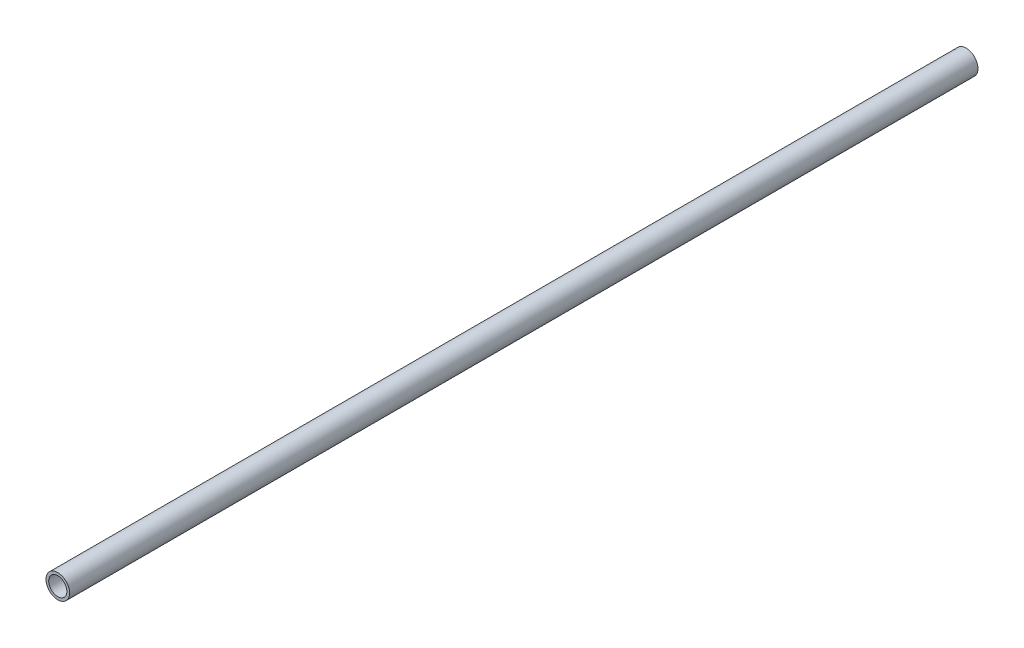
SolidWorks part; units mm, degrees
material "6061 Alloy"
ref_plane "Front Plane" through (0, 0, 0) normal (0, 0, 1) x (1, 0, 0)
ref_plane "Top Plane" through (0, 0, 0) normal (0, 1, 0) x (1, 0, 0)
ref_plane "Right Plane" through (0, 0, 0) normal (1, 0, 0) x (0, 0, -1)
sketch "Sketch1" plane through (0, 0, 0) normal (0, 0, 1) x (1, 0, 0)
  circle A0 centre (390.7614, 31.0815) radius 6.5
  circle A1 centre (390.7614, 31.0815) radius 5
extrude "Boss-Extrude1" add sketch "Sketch1" along normal blind 500
